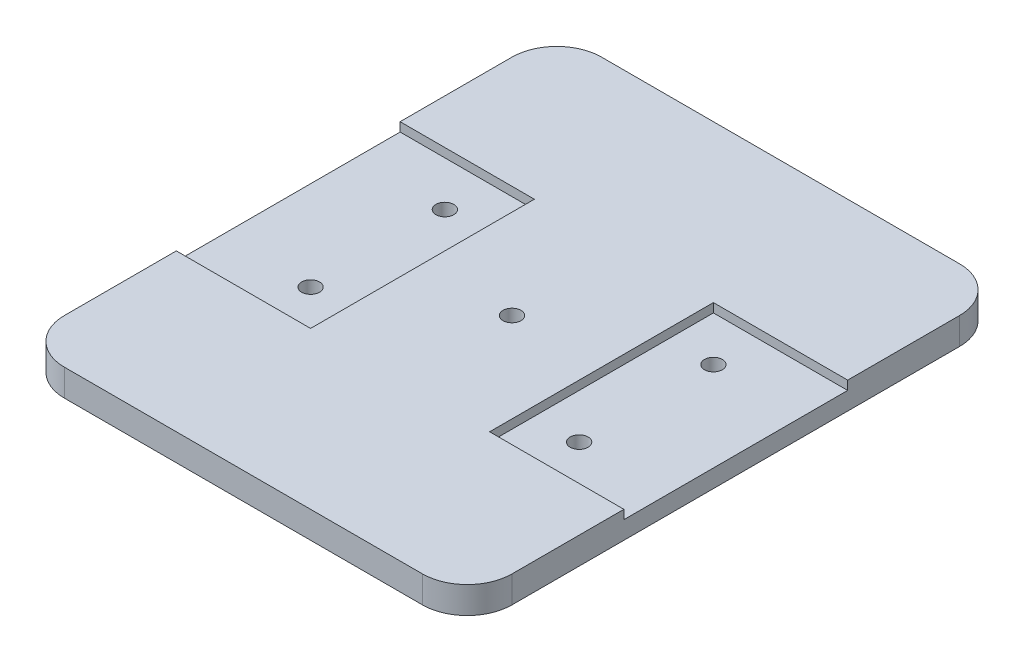
SolidWorks part; units mm, degrees
ref_plane "Front Plane" through (0, 0, 0) normal (0, 0, 1) x (1, 0, 0)
ref_plane "Top Plane" through (0, 0, 0) normal (0, 1, 0) x (1, 0, 0)
ref_plane "Right Plane" through (0, 0, 0) normal (1, 0, 0) x (0, 0, -1)
sketch "Sketch1" plane through (0, 0, 0) normal (0, 1, 0) x (1, 0, 0)
  line L1 (-52.2549, 26.2745) -> (-12.2549, 26.2745)
  line L2 (-57.2549, 21.2745) -> (-57.2549, -28.7255)
  line L3 (-52.2549, -33.7255) -> (-12.2549, -33.7255)
  line L4 (-7.2549, 21.2745) -> (-7.2549, -28.7255)
  arc A0 (-57.2549, -28.7255) -> (-52.2549, -33.7255) centre (-52.2549, -28.7255) ccw
  arc A1 (-12.2549, -33.7255) -> (-7.2549, -28.7255) centre (-12.2549, -28.7255) ccw
  arc A2 (-12.2549, 26.2745) -> (-7.2549, 21.2745) centre (-12.2549, 21.2745) cw
  arc A3 (-52.2549, 26.2745) -> (-57.2549, 21.2745) centre (-52.2549, 21.2745) ccw
  circle A4 centre (-32.2549, -3.7255) radius 1
  circle A5 centre (-47.2549, 3.7745) radius 1
  circle A6 centre (-47.2549, -11.2255) radius 1
  circle A7 centre (-17.2549, 3.7745) radius 1
  circle A8 centre (-17.2549, -11.2255) radius 1
  point P6 (-57.2549, -33.7255)
  point P11 (-7.2549, 26.2745)
  point P14 (-57.2549, 26.2745)
  dimension "D3" = 5
  dimension "D4" = 30
  dimension "D6" = 22.5
  dimension "D8" = 15
  dimension "D10" = 10
  dimension "D1" = 60
  dimension "D2" = 50
  dimension "D5" = 25
  dimension "D7" = 10
  dimension "D9" = 10
  dimension "D11" = 10
  dimension "D12" = 15
  dimension "D13" = 22.5
extrude "Boss-Extrude1" add sketch "Sketch1" along normal blind 3
sketch "Sketch2" plane through (0, 3, 0) normal (0, 1, 0) x (1, 0, 0)
  line L0 (-57.2549, 21.2745) -> (-57.2549, -28.7255) construction
  line L1 (-57.2549, 8.7745) -> (-42.2549, 8.7745)
  line L2 (-57.2549, 8.7745) -> (-57.2549, -16.2255)
  line L3 (-57.2549, -16.2255) -> (-42.2549, -16.2255)
  line L4 (-42.2549, 8.7745) -> (-42.2549, -16.2255)
  line L5 (-12.2549, 26.2745) -> (-52.2549, 26.2745) construction
  dimension "D1" = 17.5
  dimension "D2" = 25
  dimension "D3" = 15
extrude "Cut-Extrude1" cut sketch "Sketch2" against normal blind 1
sketch "Sketch3" plane through (0, 3, 0) normal (0, 1, 0) x (1, 0, 0)
  line L0 (-7.2549, -28.7255) -> (-7.2549, 21.2745) construction
  line L1 (-7.2549, 8.7745) -> (-22.2549, 8.7745)
  line L2 (-7.2549, 8.7745) -> (-7.2549, -16.2255)
  line L3 (-7.2549, -16.2255) -> (-22.2549, -16.2255)
  line L4 (-22.2549, 8.7745) -> (-22.2549, -16.2255)
  line L5 (-12.2549, 26.2745) -> (-52.2549, 26.2745) construction
  dimension "D1" = 15
  dimension "D2" = 25
  dimension "D3" = 17.5
extrude "Cut-Extrude2" cut sketch "Sketch3" against normal blind 1
